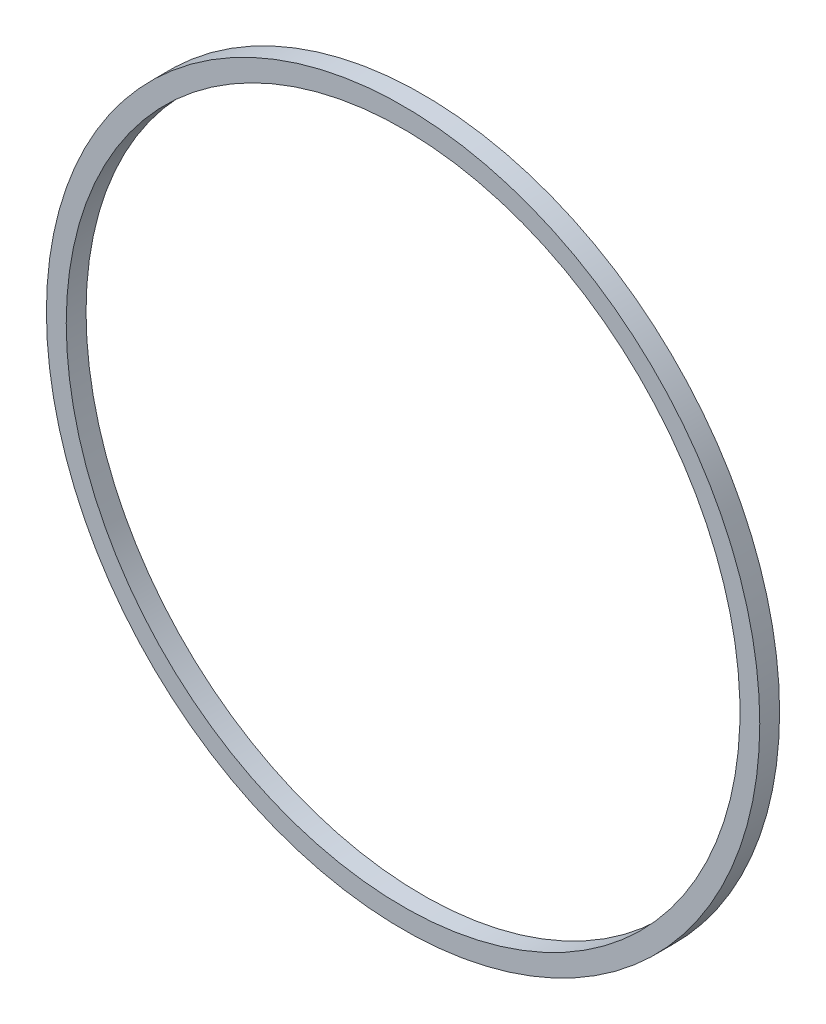
SolidWorks part; units mm, degrees
ref_plane "Front Plane" through (0, 0, 0) normal (0, 0, 1) x (1, 0, 0)
ref_plane "Top Plane" through (0, 0, 0) normal (0, 1, 0) x (1, 0, 0)
ref_plane "Right Plane" through (0, 0, 0) normal (1, 0, 0) x (0, 0, -1)
sketch "Sketch1" plane through (0, 0, 0) normal (0, 0, 1) x (1, 0, 0)
  circle A0 centre (0, 0) radius 666.75
  dimension "D1" = 1333.5
sketch "Sketch2" plane through (0, 0, 0) normal (0, 1, 0) x (1, 0, 0)
  line L0 (-666.75, 0) -> (666.75, 0) construction
  line L1 (-685.8, -19.05) -> (-647.7, -19.05)
  line L2 (-685.8, -19.05) -> (-685.8, 19.05)
  line L3 (-685.8, 19.05) -> (-647.7, 19.05)
  line L4 (-647.7, -19.05) -> (-647.7, 19.05)
  line L5 (-685.8, -19.05) -> (-647.7, 19.05) construction
  line L6 (-685.8, 19.05) -> (-647.7, -19.05) construction
  point P0 (-666.75, 0)
  dimension "D1" = 666.75
  dimension "D2" = 38.1
sweep "Sweep1" add profiles "Sketch2" path "Sketch1"
